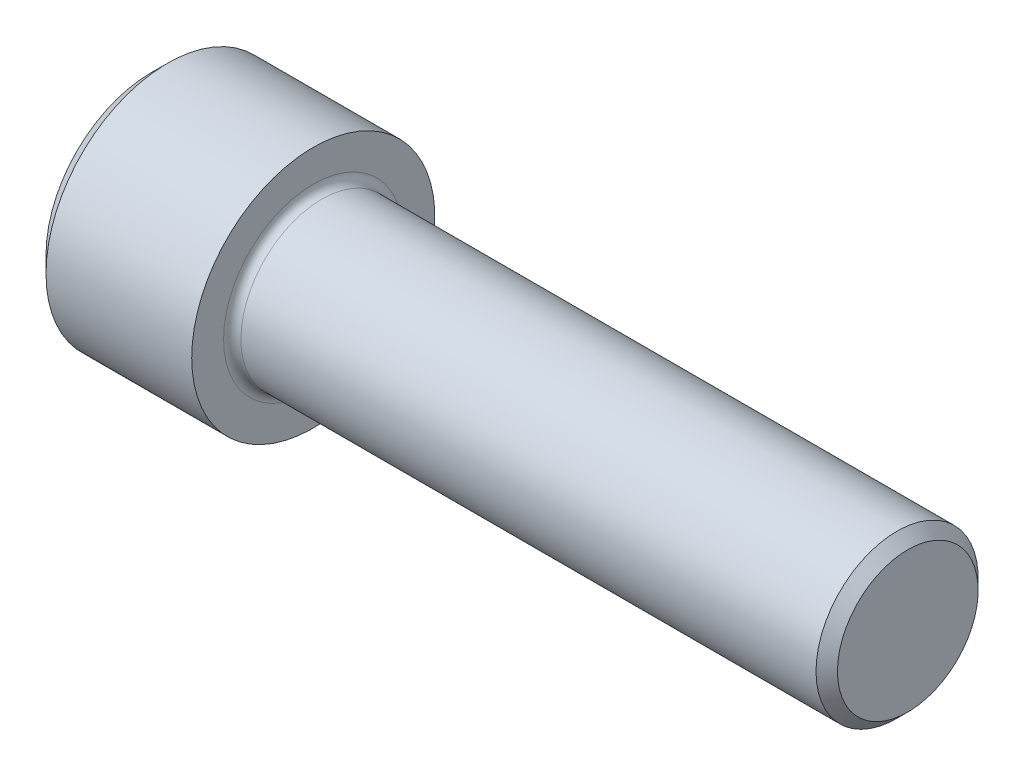
SolidWorks part; units mm, degrees
revolve "Base-Revolve" add sketch "BodySke"
sketch "BodySke" plane through (0, 0, 0) normal (0, 0, 1) x (1, 0, 0)
  line L0 (0, 0) -> (0, 6.1786)
  line L1 (0.9652, 7.1437) -> (9.525, 7.1437)
  line L2 (9.525, 7.1437) -> (9.525, 4.7625)
  line L3 (9.525, 4.7625) -> (43.8201, 4.7625)
  line L4 (44.45, 4.1326) -> (44.45, 0)
  line L5 (44.45, 0) -> (0, 0)
  line L6 (-31.75, 0) -> (127, 0) construction
  line L7 (0, 6.1786) -> (0.9652, 7.1437)
  line L8 (44.45, 4.1326) -> (43.8201, 4.7625)
  line L9 (0, -6.1786) -> (0.9652, -7.1438) construction
  line L10 (44.45, -4.1326) -> (43.8201, -4.7625) construction
  line L11 (10.5842, 9.525) -> (10.5842, 3.175) construction
  line L12 (9.525, 9.525) -> (9.525, 3.175) construction
  line L13 (6.35, 9.525) -> (6.35, 3.175) construction
  dimension "Diameter" = 9.525
  dimension "Head_ht" = 9.525
  dimension "Length" = 34.925
  dimension "Body_ch_ang" = 45
  dimension "Head_dia" = 14.2875
  dimension "Head_ch_ang" = 45
  dimension "Head_side_ht" = 8.5598
  dimension "Minor_dia" = 8.2652
  dimension "Advance" = 1.0592
  dimension "Thread_nom" = 34.925
  dimension "Thread_length" = 38.1
cosmetic thread "ThreadCosmetic" [suppressed]
fillet "Fillet1" radius 0.508 1 edges at (9.525, 0, 4.7625)
ref_plane "Plane1" through (0, 0, 0) normal (0, 0, 1) x (1, 0, 0)
ref_plane "Plane2" through (0, 0, 0) normal (0, 1, 0) x (1, 0, 0)
ref_plane "Plane3" through (0, 0, 0) normal (1, 0, 0) x (0, 0, -1)
sketch "Sketch2" plane through (0, 0, 0) normal (0, 0, 1) x (1, 0, 0)
  line L0 (0, 3.9688) -> (4.6228, 3.9688)
  line L1 (4.6228, 3.9688) -> (6.9142, 0)
  line L2 (-31.75, 0) -> (127, 0) construction
  line L3 (6.9142, 0) -> (0, 0)
  line L4 (0, 0) -> (0, 3.9688)
  line L5 (0, 6.1786) -> (0, -6.1786) construction
  line L6 (0, 0) -> (47.625, 0) construction
  line L7 (9.525, -7.1437) -> (9.525, 7.1437) construction
  dimension "D1" = 3.9688
  dimension "D2" = 60
revolve "Hex-PreBroach" cut sketch "Sketch2" angle 360 about L6
sketch "Sketch3" plane through (0, 0, 0) normal (-1, 0, 0) x (0, 0.5, 0.866)
  line L0 (2.2914, 3.9688) -> (-2.2914, 3.9688)
  line L1 (-2.2914, 3.9688) -> (-4.5827, 0)
  line L2 (2.2914, 3.9688) -> (4.5827, 0)
  line L3 (2.2914, -3.9687) -> (4.5827, 0)
  line L4 (2.2914, -3.9687) -> (-2.2914, -3.9687)
  line L5 (-2.2914, -3.9687) -> (-4.5827, 0)
  dimension "D1" = 3.9688
  dimension "D2" = 3.9688
  dimension "Hex_size" = 7.9375
extrude "Hex" cut sketch "Sketch3" against normal blind 4.6228
sketch "Sketch4" plane through (0, 0, 0) normal (-1, 0, 0) x (0, 0, 1)
  line L0 (0, 0) -> (4.826, 0)
  line L1 (0, 0) -> (6.1484, 3.5498) construction
  line L2 (0, 0) -> (2.413, 4.1794)
  line L3 (3.9437, 0.9277) -> (4.6393, 1.3293)
  line L4 (2.7753, 2.9514) -> (3.4709, 3.3531)
  arc A0 (3.9437, 0.9277) -> (2.7753, 2.9514) centre (0, 0) ccw
  arc A1 (4.826, 0) -> (4.6393, 1.3293) centre (0, 0) ccw
  arc A2 (2.413, 4.1794) -> (3.4709, 3.3531) centre (0, 0) cw
  dimension "D1" = 30
  dimension "D2" = 60
  dimension "Spline_p_dim" = 2.3368
  dimension "D3" = 1.1684
extrude "Spline" [suppressed] cut sketch "Sketch4" against normal blind 4.6228
pattern_circular "CirPattern1" [suppressed] count 6 every 60
sketch "Sketch5" plane through (0, 0, 0) normal (0, 0, 1) x (1, 0, 0)
  line L0 (-31.75, 0) -> (127, 0) construction
  line L2 (0, 6.1786) -> (0, -6.1786) construction
  circle A0 centre (3.1242, 0) radius 0.8065
  dimension "Drilled_hole_dia" = 1.6129
  dimension "Drilled_hole_loc" = 3.1242
extrude "Hole" [suppressed] cut sketch "Sketch5" against normal through all and the other way through all
pattern_circular "Drilled-4" [suppressed] count 2 every 60
pattern_circular "Drilled-6" [suppressed] count 3 every 60
sketch "ThdSchSke" plane through (0, 0, 0) normal (0, 0, 1) x (1, 0, 0)
  line L0 (10.5842, -4.1326) -> (10.1431, -4.7625)
  line L1 (10.5842, -4.1326) -> (11.0253, -4.7625)
  line L2 (11.0253, -4.7625) -> (11.0253, -5.9531)
  line L3 (-3.175, 0) -> (5.1513, 0) construction
  line L5 (11.0253, -5.9531) -> (10.1431, -5.9531)
  line L6 (10.1431, -5.9531) -> (10.1431, -4.7625)
  line L7 (0, 6.1786) -> (0, -6.1786) construction
  dimension "Thread_minor" = 8.2652
  dimension "Diameter" = 9.525
  dimension "Start" = 10.5842
revolve "ThreadSchematic" [suppressed] cut sketch "ThdSchSke" angle 360 about L3
pattern_linear "ThdSchPat" [suppressed]
equation "\"D2@Sketch3\" = \"Hex_size@Sketch3\" / 2"
equation "\"D1@Sketch3\" = \"Hex_size@Sketch3\" / 2"
equation "\"D1@Sketch2\" = \"Hex_size@Sketch3\" / 2"
equation "\"D3@Sketch4\" = \"Spline_p_dim@Sketch4\" / 2"
equation "\"Thread_minor@ThreadCosmetic\"  =  \"Minor_dia@BodySke\""
equation "\"D2@CirPattern1\" = 360 / \"Num_teeth@CirPattern1\""
equation "\"Wall_thickness@Sketch2\" = \"Head_ht@BodySke\" - \"Key_eng@Hex\""
equation "\"Thread_length@ThreadCosmetic\" = ((sgn( (\"Length@BodySke\" - \"Advance@BodySke\" ) - \"Thread_nom@BodySke\" )-1)*( (\"Length@BodySke\" - \"Advance@BodySke\" ) - \"Thread_nom@BodySke\" ))/-2+ \"Thread_nom@BodySke\""
equation "\"Thread_minor@ThdSchSke\" = \"Minor_dia@BodySke\""
equation "\"Diameter@ThdSchSke\" = \"Diameter@BodySke\""
equation "\"Overcut@ThdSchSke\" = \"Diameter@BodySke\" * 1.25"
equation "\"Start@ThdSchSke\" = \"Head_ht@BodySke\" + \"Length@BodySke\" - \"Thread_length@ThreadCosmetic\"  '---Non-countersunk---"
equation "\"Num_threads@ThdSchPat\" = int( \"Thread_length@ThreadCosmetic\" / \"Advance@BodySke\" + 0.999 )  + 1"
equation "\"Advance@ThdSchPat\" = \"Thread_length@ThreadCosmetic\" /  (\"Num_threads@ThdSchPat\" - 1) 'relax it"
equation "\"Num_threads@ThdSchPat\" = \"Num_threads@ThdSchPat\" - sgn( \"Num_threads@ThdSchPat\" - 1) '---chamfered tips only---"
